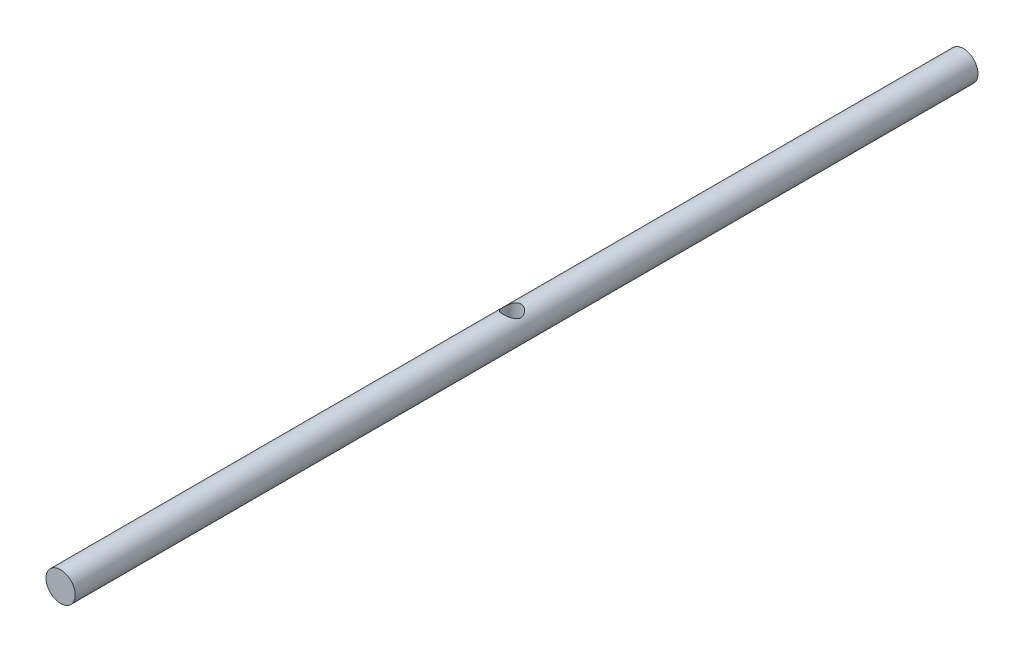
SolidWorks part; units mm, degrees
ref_plane "Plano frontal" through (0, 0, 0) normal (0, 0, 1) x (1, 0, 0)
ref_plane "Plano superior" through (0, 0, 0) normal (0, 1, 0) x (1, 0, 0)
ref_plane "Plano direito" through (0, 0, 0) normal (1, 0, 0) x (0, 0, -1)
sketch "Esboço1" plane through (0, 0, 0) normal (0, 0, 1) x (1, 0, 0)
  circle A0 centre (0, 0) radius 6.255
  dimension "D1" = 12.51
extrude "Ressalto-extrusão1" add sketch "Esboço1" along normal blind 386
ref_plane "Plano1" through (0, 10, 0) normal (0, 1, 0) x (1, 0, 0)
sketch "Esboço2" plane through (0, 10, 0) normal (0, 1, 0) x (1, 0, 0)
  line L0 (6.255, -386) -> (6.255, 0) construction
  line L2 (6.255, 0) -> (-6.255, 0) construction
  circle A0 centre (-0.0205, -193) radius 3.8315
  dimension "D1" = 7.663
  dimension "D2" = 6.2755
  dimension "D3" = 193
extrude "Corte-extrusão1" cut sketch "Esboço2" against normal through all
